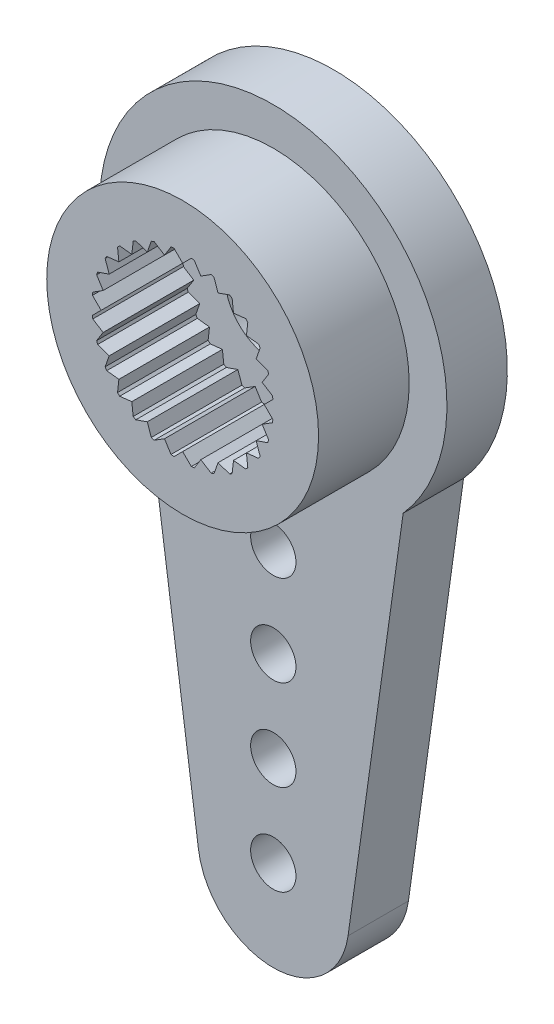
SolidWorks part; units mm, degrees
ref_plane "Plan de face" through (0, 0, 0) normal (0, 0, 1) x (1, 0, 0)
ref_plane "Plan de dessus" through (0, 0, 0) normal (0, 1, 0) x (1, 0, 0)
ref_plane "Plan de droite" through (0, 0, 0) normal (1, 0, 0) x (0, 0, -1)
sketch "Esquisse1" plane through (0, 0, 0) normal (0, 0, 1) x (1, 0, 0)
  circle A0 centre (0, 0) radius 5.75
  circle A1 centre (0, 0) radius 1.6
  dimension "D1" = 11.5
  dimension "D2" = 3.2
extrude "Boss.-Extru.1" add sketch "Esquisse1" along normal blind 5
sketch "Esquisse2" plane through (0, 0, 5) normal (0, 0, 1) x (1, 0, 0)
  circle A0 centre (0, 0) radius 3
  dimension "D1" = 6
extrude "Enlèv. mat.-Extru.1" cut sketch "Esquisse2" against normal blind 3
sketch "Esquisse3" plane through (0, 0, 5) normal (0, 0, 1) x (1, 0, 0)
  circle A0 centre (0, 0) radius 5.75
  circle A1 centre (0, 0) radius 4.5
  circle A2 centre (0, 0) radius 3 construction
  circle A3 centre (0, 0) radius 5.75 construction
  dimension "D1" = 1.5
extrude "Enlèv. mat.-Extru.2" cut sketch "Esquisse3" against normal blind 3
sketch "Esquisse4" plane through (0, 0, 0) normal (0, 0, -1) x (-1, 0, 0)
  line L0 (-4.3, 3.8174) -> (-2.4759, 16.8466)
  line L1 (2.4759, 16.8466) -> (4.3, 3.8174)
  line L2 (-5.2729, 19) -> (6.8365, 19) construction
  line L3 (0, 0) -> (0, 24.2526) construction
  circle A0 centre (0, 0) radius 5.75 construction
  arc A1 (-2.4759, 16.8466) -> (2.4759, 16.8466) centre (0, 16.5) cw
  arc A2 (-4.3, 3.8174) -> (4.3, 3.8174) centre (0, 0) cw
  dimension "D2" = 2.5
  dimension "D1" = 8.6
  dimension "D3" = 19
extrude "Boss.-Extru.2" add sketch "Esquisse4" against normal up to surface (2 mm away) up to face at (4.5, 0, 2)
pattern_circular "Répétition circulaire1" count 2 every 180 about axis through (0, 0, 0) along (0, 0, 1) of "Boss.-Extru.2"
sketch "Esquisse5" plane through (0, 0, 0) normal (0, 0, -1) x (-1, 0, 0)
  line L0 (0, 0) -> (0, 20.4605) construction
  circle A0 centre (0, 7) radius 0.75
  circle A1 centre (0, 10) radius 0.75
  circle A2 centre (0, 13) radius 0.75
  circle A3 centre (0, 16) radius 0.75
  dimension "D5" = 1.5
  dimension "D6" = 1.5
  dimension "D7" = 1.5
  dimension "D8" = 1.5
  dimension "D1" = 7
  dimension "D2" = 3
  dimension "D3" = 3
  dimension "D4" = 3
extrude "Enlèv. mat.-Extru.3" cut sketch "Esquisse5" against normal blind 3
pattern_circular "Répétition circulaire2" count 2 every 180 about axis through (0, 0, 0) along (0, 0, 1) of "Enlèv. mat.-Extru.3"
sketch "Esquisse6" plane through (0, 0, 5) normal (0, 0, 1) x (1, 0, 0)
  line L0 (-1.598, 3) -> (1.8482, 3) construction
  line L1 (0, 0) -> (0, 5.9454) construction
  line L2 (-0.3, 3) -> (0, 2.7)
  line L3 (0, 2.7) -> (0.3, 3)
  line L4 (0.3, 3) -> (-0.3, 3)
  circle A0 centre (0, 0) radius 3 construction
  dimension "D1" = 0.3
  dimension "D2" = 0.6
extrude "Boss.-Extru.3" add sketch "Esquisse6" against normal up to surface (3 mm away) up to face at (1.6, 0, 2)
pattern_circular "Répétition circulaire3" count 28 over 360 about axis through (0, 0, 0) along (0, 0, 1) of "Boss.-Extru.3"
sketch "Esquisse7" plane through (0, 0, 0) normal (0, 0, -1) x (-1, 0, 0)
  circle A0 centre (0, 0) radius 1.6
  circle A1 centre (0, 0) radius 3
  circle A2 centre (0, 0) radius 1.6 construction
  dimension "D1" = 6
extrude "Enlèv. mat.-Extru.4" cut sketch "Esquisse7" against normal blind 1
sketch "Esquisse8" plane through (0, 0, 0) normal (0, 0, -1) x (-1, 0, 0)
  circle A0 centre (0, 0) radius 3.4
  circle A1 centre (0, 0) radius 4.7
  circle A2 centre (0, 0) radius 3 construction
  dimension "D1" = 0.4
  dimension "D2" = 1.3
extrude "Enlèv. mat.-Extru.5" cut sketch "Esquisse8" against normal blind 1
sketch "Sketch1" plane through (0, 0, 0) normal (0, 0, -1) x (-1, 0, 0)
  line L1 (-4.3, 3.8174) -> (4.797, 3.8174)
  line L2 (-4.3, 3.8174) -> (-4.3, 20.07)
  line L3 (-4.3, 20.07) -> (4.797, 20.07)
  line L4 (4.797, 3.8174) -> (4.797, 20.07)
  circle A0 centre (0, 0) radius 5.75
  circle M6 centre (0, 7) radius 0.75
  circle M7 centre (0, 10) radius 0.75
  circle M8 centre (0, 13) radius 0.75
  circle M9 centre (0, 16) radius 0.75
  line M11 (4.3, 3.8174) -> (2.4759, 16.8466)
  arc M12 (2.4759, 16.8466) -> (-2.4759, 16.8466) centre (0, 16.5) ccw
  line M13 (-2.4759, 16.8466) -> (-4.3, 3.8174)
extrude "Cut-Extrude1" cut sketch "Sketch1" against normal blind 10 contours A0 M11 M12 M13 M7 M9 M8 M6
